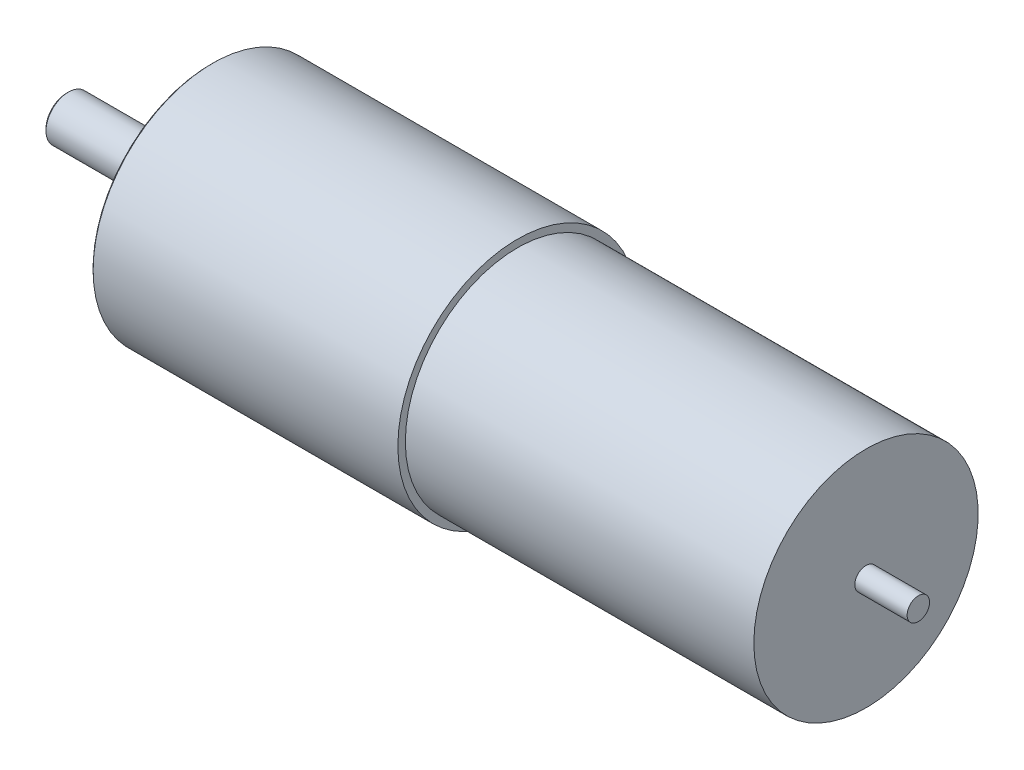
SolidWorks part; units mm, degrees
ref_plane "Front Plane" through (0, 0, 0) normal (0, 0, 1) x (1, 0, 0)
ref_plane "Top Plane" through (0, 0, 0) normal (0, 1, 0) x (1, 0, 0)
ref_plane "Right Plane" through (0, 0, 0) normal (1, 0, 0) x (0, 0, -1)
sketch "Sketch1" plane through (0, 0, 0) normal (0, 1, 0) x (1, 0, 0)
  line L0 (0, 0) -> (113.9, 0)
  line L1 (0, 0) -> (0, 3)
  line L2 (0, 3) -> (16.3, 3)
  line L3 (16.3, 3) -> (16.3, 10)
  line L4 (16.3, 10) -> (19.3, 10)
  line L5 (19.3, 10) -> (19.3, 16)
  line L6 (19.3, 16) -> (60.3, 16)
  line L7 (60.3, 16) -> (60.3, 15)
  line L8 (60.3, 15) -> (106.9, 15)
  line L9 (106.9, 15) -> (106.9, 1.5)
  line L12 (106.9, 1.5) -> (113.9, 1.5)
  line L13 (113.9, 1.5) -> (113.9, 0)
  point P3 (0, 0)
  dimension "D1" = 113.9
  dimension "D2" = 3
  dimension "D3" = 16.3
  dimension "D4" = 10
  dimension "D5" = 16
  dimension "D6" = 3
  dimension "D7" = 15
  dimension "D8" = 41
  dimension "D9" = 46.6
  dimension "D10" = 1.5
revolve "Revolve1" add sketch "Sketch1" angle 360 about L0
sketch "Sketch2" plane through (0, 0, 0) normal (0, 1, 0) x (1, 0, 0)
  line L0 (16.3, 3) -> (0, 3) construction
  line L1 (0, 3) -> (12, 3)
  line L2 (0, 3) -> (0, 2.5)
  line L3 (0, 2.5) -> (12, 2.5)
  line L4 (12, 3) -> (12, 2.5)
  line L5 (0, 3) -> (0, -3) construction
  line L6 (0, -3) -> (16.3, -3) construction
  dimension "D1" = 12
  dimension "D2" = 5.5
extrude "Cut-Extrude1" cut sketch "Sketch2" against normal through all both and the other way through all
chamfer "Chamfer1" distance 0.25 angle 45 2 edges at (19.3, 0, 16) (0, 0, 3)
sketch "Sketch3" plane through (16.3, 0, 0) normal (-1, 0, 0) x (0, 0, 1)
  line L0 (10, 9) -> (-10, 9)
  line L1 (-10, -9) -> (10, -9)
  line L2 (-10, -9) -> (-10, 9) construction
  line L3 (10, -9) -> (10, 9) construction
  line L4 (-10, 9) -> (-10, 11)
  line L5 (-10, 11) -> (10, 11)
  line L6 (10, 11) -> (10, 9)
  line L7 (-10, -9) -> (-10, -11)
  line L8 (-10, -11) -> (10, -11)
  line L9 (10, -11) -> (10, -9)
  circle A0 centre (0, 0) radius 10 construction
  circle A1 centre (0, 0) radius 10 construction
  point P8 (-10, 0)
  dimension "D1" = 18
  dimension "D2" = 2
  dimension "D3" = 2
extrude "Cut-Extrude2" cut sketch "Sketch3" against normal up to surface (3 mm away) up to face at (19.3, 0, -15.75)
sketch "Sketch4" plane through (19.3, 0, 0) normal (-1, 0, 0) x (0, 0, 1)
  line L0 (-9.1924, 9.1924) -> (0, 0) construction
  line L1 (0, 0) -> (-16, 0) construction
  circle A0 centre (0, 0) radius 16 construction
  circle A1 centre (0, 0) radius 13 construction
  point P0 (-9.1924, 9.1924)
  point P8 (0, 0)
  point P9 (9.1924, 9.1924)
  point P10 (0, 0)
  point P11 (0, 0)
  point P12 (9.1924, -9.1924)
  point P13 (-9.1924, -9.1924)
  point P14 (0, 0)
  dimension "D2" = 26
  dimension "D1" = 45
  dimension "D4" = 13
  dimension "D5" = 13
  dimension "D3" = 4
hole_wizard "M3x0.5 Tapped Hole1" positions "Sketch5" profile "Sketch7" tap size "M3x0.5" standard "ANSI Metric"
sketch "Sketch5" plane through (19.3, 0, 0) normal (-1, 0, 0) x (0, 0, 1)
  point P0 (-9.1924, -9.1924)
  point P3 (-9.1924, 9.1924)
  point P6 (9.1924, 9.1924)
  point P9 (9.1924, -9.1924)
sketch "Sketch7" plane through (19.3, -9.1924, -9.1924) normal (0, 1, 0) x (0, 0, 1)
  line L0 (0, 0) -> (0, 6.2511)
  line L1 (0, 6.2511) -> (1.25, 5.5)
  line L2 (1.25, 5.5) -> (1.25, 0)
  line L5 (1.25, 0) -> (0, 0)
  line L10 (0, 6.2511) -> (-1.25, 5.5) construction
  line L11 (0, -6.35) -> (0, 107.95) construction
  dimension "Tap Drill Dia." = 2.5
  dimension "Tap Drill Depth" = 5.5
  dimension "Drill Angle" = 118
cosmetic thread "Hole Thread1" parameters "D1"=5.5, "D2"=3
cosmetic thread "Hole Thread2" parameters "D1"=5.5, "D2"=3
cosmetic thread "Hole Thread3" parameters "D1"=5.5, "D2"=3
cosmetic thread "Hole Thread4" parameters "D1"=5.5, "D2"=3
